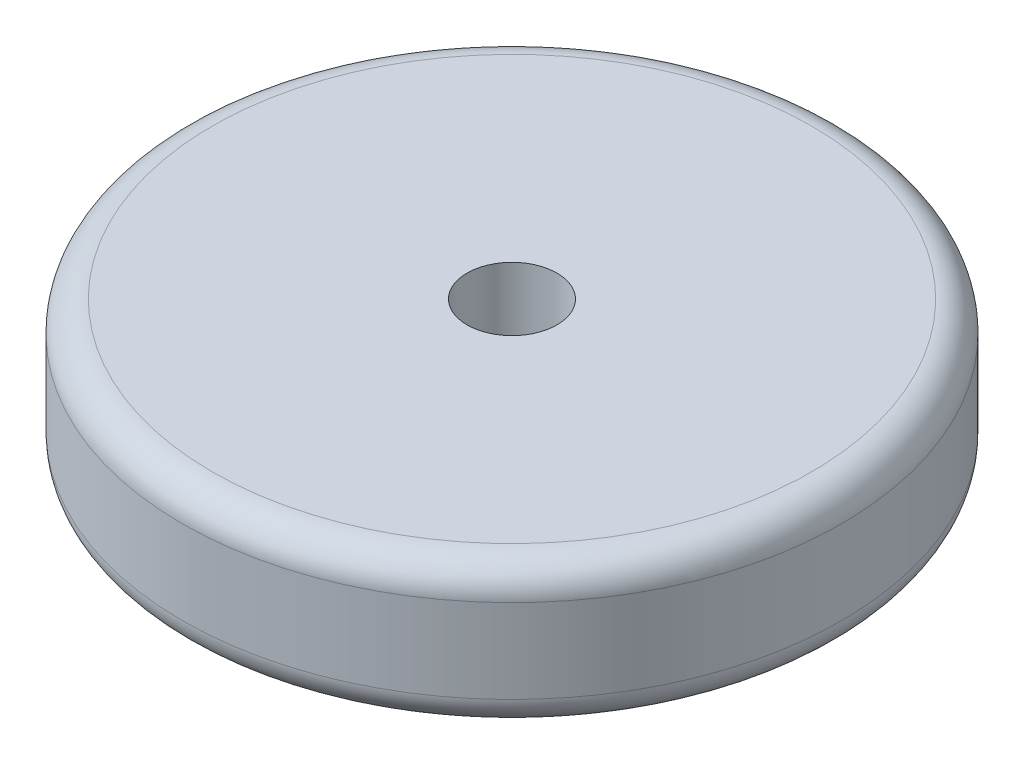
SolidWorks part; units mm, degrees
material "ALUMINUM 6061-T6"
ref_plane "Front Plane" through (0, 0, 0) normal (0, 0, 1) x (1, 0, 0)
ref_plane "Top Plane" through (0, 0, 0) normal (0, 1, 0) x (1, 0, 0)
ref_plane "Right Plane" through (0, 0, 0) normal (1, 0, 0) x (0, 0, -1)
sketch "Sketch1" plane through (0, 0, 0) normal (0, 1, 0) x (1, 0, 0)
  circle A0 centre (0, 0) radius 69.85
  dimension "D1" = 139.7
extrude "Boss-Extrude1" add sketch "Sketch1" along normal mid plane 30.48
sketch "Sketch2" plane through (0, 15.24, 0) normal (0, 1, 0) x (1, 0, 0)
  circle A0 centre (0, 0) radius 9.525
  dimension "D1" = 19.05
extrude "Cut-Extrude1" cut sketch "Sketch2" against normal blind 30.48
fillet "Fillet1" radius 6.35 2 edges at (0, -15.24, 69.85) (0, 15.24, 69.85)
